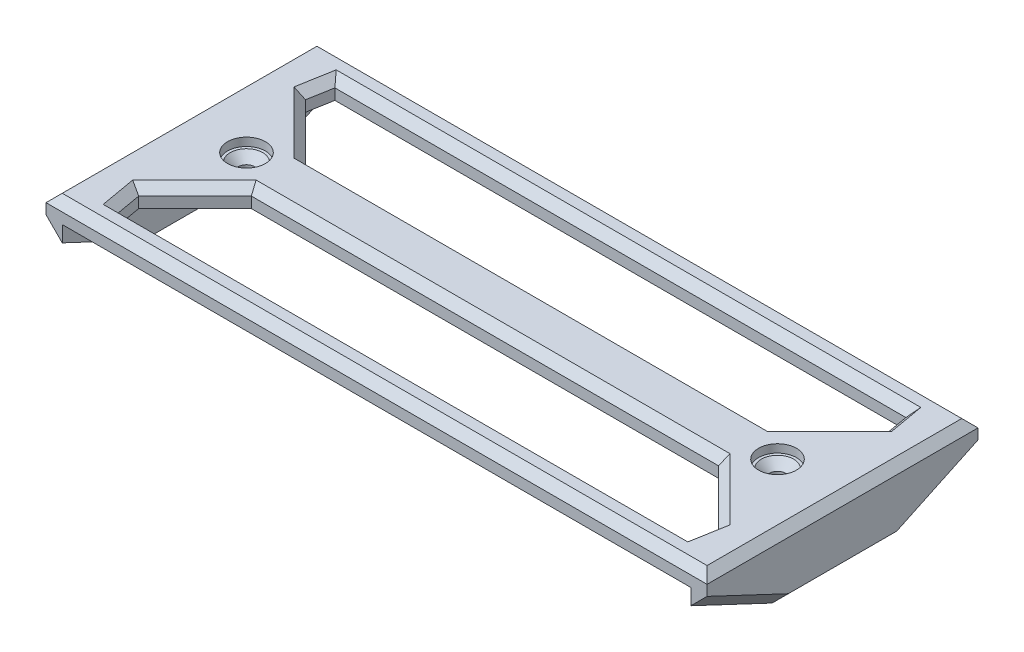
SolidWorks part; units mm, degrees
ref_plane "Front Plane" through (0, 0, 0) normal (0, 0, 1) x (1, 0, 0)
ref_plane "Top Plane" through (0, 0, 0) normal (0, 1, 0) x (1, 0, 0)
ref_plane "Right Plane" through (0, 0, 0) normal (1, 0, 0) x (0, 0, -1)
sketch "Sketch1" plane through (0, 0, 0) normal (0, 0, 1) x (1, 0, 0)
  line L0 (-58, 0) -> (58, 0)
  line L1 (-58, 0) -> (-58, -10)
  line L2 (-58, -10) -> (-61, -7)
  line L3 (-61, -7) -> (-61, 3.5)
  line L4 (-61, 3.5) -> (61, 3.5)
  line L5 (0, 0) -> (0, 50000) construction
  line L6 (58, 0) -> (58, -10)
  line L7 (58, -10) -> (61, -7)
  line L8 (61, -7) -> (61, 3.5)
  point P4 (0, 0)
  point P14 (0, 3.5)
  dimension "D1" = 116
  dimension "D2" = 3.5
  dimension "D3" = 3
  dimension "D4" = 45
  dimension "D5" = 10
extrude "Boss-Extrude1" add sketch "Sketch1" along normal mid plane 20
ref_plane "Plane1" through (0, 0, -25) normal (0, 0, 1) x (1, 0, 0)
sketch "Sketch4" plane through (0, 0, -25) normal (0, 0, 1) x (1, 0, 0)
  line L0 (58, -2.9289) -> (61, 0.0711)
  line L1 (-58, -2.9289) -> (-61, 0.0711)
  line L2 (54.4645, -6.4645) -> (57.4645, -3.4645) construction
  line L3 (61, -7) -> (61, 3.5) construction
  line L4 (58, 0) -> (58, -10) construction
  line L5 (-57.4645, -3.4645) -> (-54.4645, -6.4645) construction
  line L6 (-61, 3.5) -> (-61, -7) construction
  line L7 (-58, -10) -> (-58, 0) construction
  line L8 (58, 0) -> (58, -10)
  line L9 (-58, 0) -> (58, 0)
  line L10 (-58, -10) -> (-58, 0)
  line L11 (-61, -7) -> (-58, -10)
  line L12 (-61, 3.5) -> (-61, -7)
  line L13 (61, 3.5) -> (-61, 3.5)
  line L14 (61, -7) -> (61, 3.5)
  line L15 (58, -10) -> (61, -7)
  line L16 (58, 0) -> (58, -2.9289)
  line L17 (-58, 0) -> (58, 0)
  line L18 (-58, -2.9289) -> (-58, 0)
  line L19 (-61, -7) -> (-58, -10) construction
  line L20 (-61, 3.5) -> (-61, 0.0711)
  line L21 (61, 3.5) -> (-61, 3.5)
  line L22 (61, 0.0711) -> (61, 3.5)
  line L23 (58, -10) -> (61, -7) construction
  dimension "D1" = 0
  dimension "D2" = 5
loft "Loft1" add profiles "Sketch4" section "Sketch4" section face at (0, -3.375, -10)
ref_plane "Plane2" through (0, 0, 25) normal (0, 0, 1) x (1, 0, 0)
sketch "Sketch5" plane through (0, 0, 25) normal (0, 0, 1) x (1, 0, 0)
  line L14 (-58, 0) -> (58, 0)
  line L15 (-58, -2.9289) -> (-58, 0)
  line L24 (-61, 0.0711) -> (-58, -2.9289)
  line L25 (-61, 3.5) -> (-61, 0.0711)
  line L26 (61, 3.5) -> (-61, 3.5)
  line L27 (61, 0.0711) -> (61, 3.5)
  line L28 (58, -2.9289) -> (61, 0.0711)
  line L29 (58, 0) -> (58, -2.9289)
  line L30 (-58, 0) -> (58, 0)
  line L31 (-58, -2.9289) -> (-58, 0)
  line L32 (-61, 0.0711) -> (-58, -2.9289)
  line L33 (-61, 3.5) -> (-61, 0.0711)
  line L34 (61, 3.5) -> (-61, 3.5)
  line L35 (61, 0.0711) -> (61, 3.5)
  line L36 (58, -2.9289) -> (61, 0.0711)
  line L37 (58, 0) -> (58, -2.9289)
  dimension "D1" = 0
loft "Loft2" add profiles "Sketch5" section face at (0, -3.375, 10) section "Sketch5"
sketch "Sketch6" plane through (0, 3.5, 0) normal (0, 1, 0) x (1, 0, 0)
  line L0 (43.1077, 5) -> (-43.1077, 5)
  line L19 (-43.1077, 5) -> (-53.5, 15.3923)
  line L20 (-53.5, 15.3923) -> (-52.6875, 20)
  line L21 (-52.6875, 20) -> (52.6875, 20)
  line L22 (52.6875, 20) -> (53.5, 15.3923)
  line L23 (53.5, 15.3923) -> (43.1077, 5)
  line L24 (0, -25) -> (0, 25) construction
  line L25 (-7.4251, -25) -> (7.4251, -25) construction
  line L26 (-7.4251, 25) -> (7.4251, 25) construction
  line L27 (61, -25) -> (61, 25) construction
  line L28 (43.1077, -5) -> (-43.1077, -5)
  line L29 (-43.1077, -5) -> (-53.5, -15.3923)
  line L30 (-53.5, -15.3923) -> (-52.6875, -20)
  line L31 (-52.6875, -20) -> (52.6875, -20)
  line L32 (52.6875, -20) -> (53.5, -15.3923)
  line L33 (53.5, -15.3923) -> (43.1077, -5)
  dimension "D2" = 105.3751
  dimension "D3" = 135
  dimension "D4" = 5
  dimension "D5" = 5
  dimension "D6" = 7.5
  dimension "D7" = 5
  dimension "D8" = 5
  dimension "D9" = 135
  dimension "D10" = 100
  dimension "D11" = 100
extrude "Cut-Extrude3" cut sketch "Sketch6" against normal through all
chamfer "Chamfer2" distance 1.5 angle 45 18 edges at (48.3038, 3.5, -10.1962) (53.0938, 3.5, -17.6962) (0, 3.5, -20) (-53.0938, 3.5, -17.6962) (-48.3038, 3.5, -10.1962) (0, 3.5, -5) (-53.0938, 3.5, 17.6962) (0, 3.5, 20) (53.0938, 3.5, 17.6962) (48.3038, 3.5, 10.1962) (0, 3.5, 5) (-48.3038, 3.5, 10.1962)
sketch "Sketch2" plane through (0, 3.5, 0) normal (0, 1, 0) x (1, 0, 0)
  line L0 (49, 0) -> (-49, 0) construction
  line L1 (0, 10) -> (0, -10) construction
  circle A0 centre (49, 0) radius 3.5
  circle A1 centre (-49, 0) radius 3.5
  point P4 (0, 0)
  point P11 (0, 0)
  dimension "D2" = 7
  dimension "D1" = 98
extrude "Cut-Extrude1" cut sketch "Sketch2" against normal offset from surface (1.5 mm away) 2 up to face at (0, 0, -13.4641)
sketch "Sketch3" plane through (0, 2, 0) normal (0, 1, 0) x (1, 0, 0)
  line L0 (0, 10) -> (0, -10) construction
  circle A0 centre (49, 0) radius 3.5 construction
  circle A1 centre (49, 0) radius 3.5 construction
  circle A2 centre (49, 0) radius 1.5
  circle A3 centre (-49, 0) radius 1.5
  point P10 (0, 0)
  dimension "D1" = 3
extrude "Cut-Extrude2" cut sketch "Sketch3" against normal through all
chamfer "Chamfer1" distance 1.5 angle 45 2 edges at (47.5, 2, 0) (-47.5, 2, 0)
